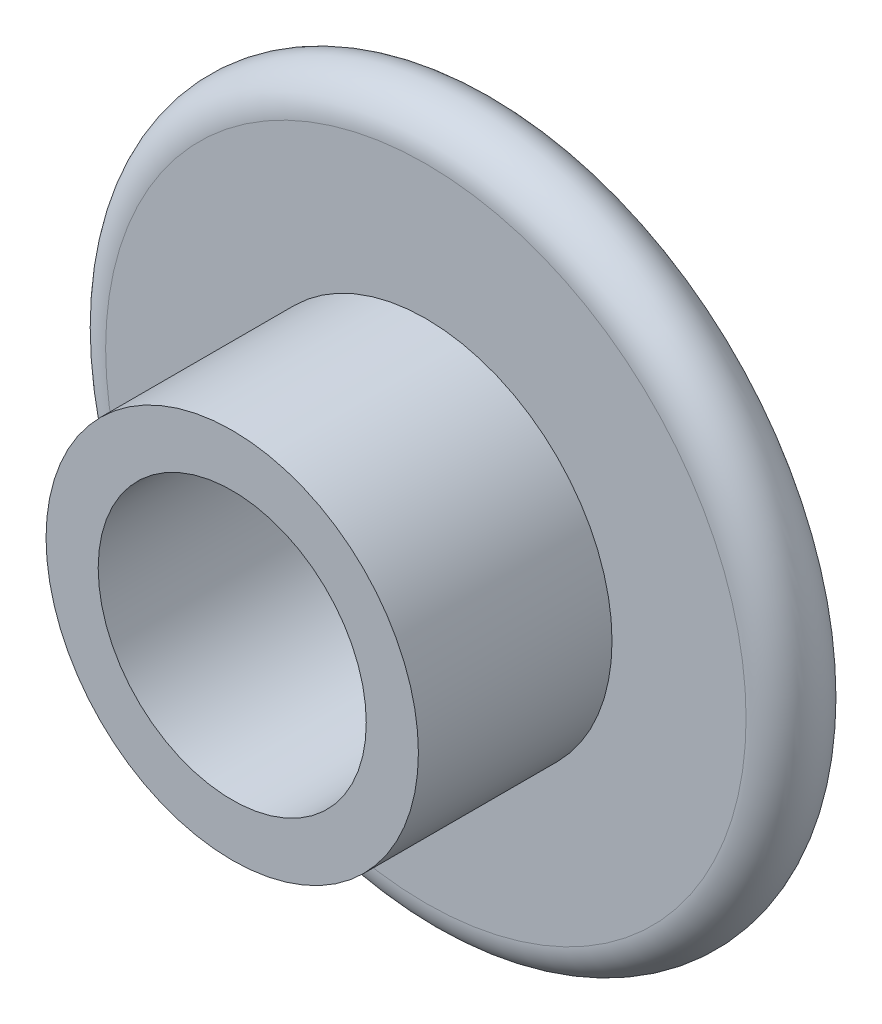
SolidWorks part; units mm, degrees
ref_plane "Front Plane" through (0, 0, 0) normal (0, 0, 1) x (1, 0, 0)
ref_plane "Top Plane" through (0, 0, 0) normal (0, 1, 0) x (1, 0, 0)
ref_plane "Right Plane" through (0, 0, 0) normal (1, 0, 0) x (0, 0, -1)
sketch "Sketch1" plane through (0, 0, 0) normal (0, 1, 0) x (1, 0, 0)
  line L0 (0, 73.9822) -> (0, -77.0891) construction
  line L1 (25, 0) -> (25, 26)
  line L2 (18, 46) -> (18, 0)
  line L3 (18, 46) -> (25, 46)
  line L4 (25, 36) -> (43, 36)
  line L6 (43, 26) -> (25, 26)
  line L7 (25, 36) -> (25, 46)
  line L8 (18, 0) -> (25, 0)
  arc A0 (43, 36) -> (43, 26) centre (43, 31) cw
  point P9 (21.5, 0)
  point P13 (48, 31)
  dimension "D6" = 48
  dimension "D1" = 46
  dimension "D2" = 25
  dimension "D3" = 18
  dimension "D4" = 10
  dimension "D5" = 10
revolve "Revolve1" add sketch "Sketch1" angle 360 about L0
